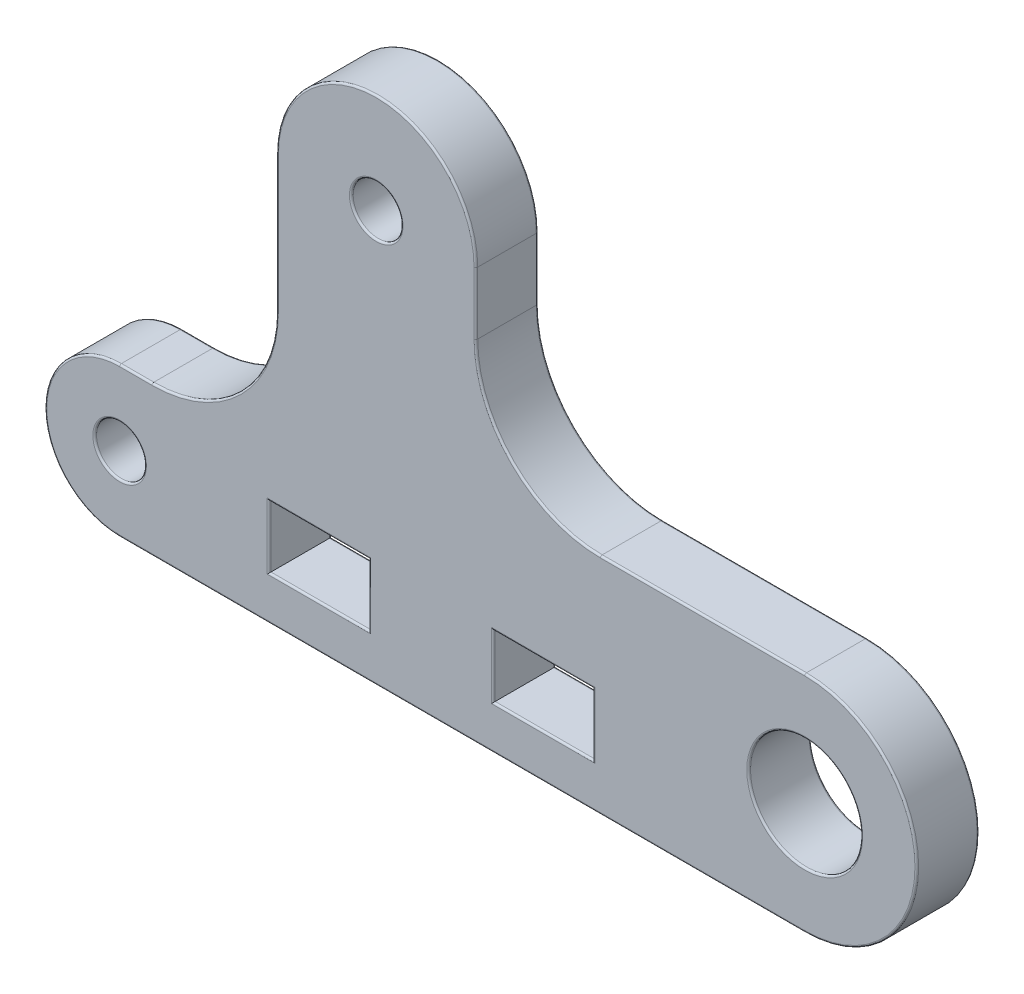
SolidWorks part; units mm, degrees
material "AISI 1020"
ref_plane "Front Plane" through (0, 0, 0) normal (0, 0, 1) x (1, 0, 0)
ref_plane "Top Plane" through (0, 0, 0) normal (0, 1, 0) x (1, 0, 0)
ref_plane "Right Plane" through (0, 0, 0) normal (1, 0, 0) x (0, 0, -1)
sketch "Sketch1" plane through (0, 0, 0) normal (0, 0, 1) x (1, 0, 0)
  line L0 (-27.5, 0) -> (27.5, 0)
  line L1 (-14.9, 33) -> (-14.9, 22)
  line L2 (-24.9, 12) -> (-27.5, 12)
  line L3 (1.1, 33) -> (1.1, 28)
  line L4 (11.1, 18) -> (27.5, 18)
  line L5 (-27.5, 6) -> (-15.5, 6) construction
  line L7 (-15.5, 3.5) -> (-7.5, 3.5)
  line L8 (-15.5, 3.5) -> (-15.5, 8.5)
  line L9 (-15.5, 8.5) -> (-7.5, 8.5)
  line L10 (-7.5, 3.5) -> (-7.5, 8.5)
  line L11 (2.5, 8.5) -> (10.5, 8.5)
  line L12 (2.5, 8.5) -> (2.5, 3.5)
  line L13 (2.5, 3.5) -> (10.5, 3.5)
  line L14 (10.5, 8.5) -> (10.5, 3.5)
  arc A0 (27.5, 0) -> (27.5, 18) centre (27.5, 9) ccw
  arc A1 (-27.5, 0) -> (-27.5, 12) centre (-27.5, 6) cw
  circle A2 centre (-27.5, 6) radius 2
  circle A3 centre (27.5, 9) radius 4.5
  circle A4 centre (-6.9, 33) radius 2
  circle A5 centre (-6.9, 33) radius 8 construction
  arc A6 (1.1, 28) -> (11.1, 18) centre (11.1, 28) ccw
  arc A7 (-14.9, 22) -> (-24.9, 12) centre (-24.9, 22) cw
  arc A8 (-14.9, 33) -> (1.1, 33) centre (-6.9, 33) cw
  point P3 (0, 0)
  dimension "D2" = 9
  dimension "D3" = 6
  dimension "D4" = 9
  dimension "D5" = 4
  dimension "D8" = 16
  dimension "D9" = 10
  dimension "D1" = 55
  dimension "D6" = 33
  dimension "D7" = 6.9
  dimension "D10" = 8
  dimension "D11" = 5
  dimension "D12" = 12
  dimension "D13" = 10
extrude "Boss-Extrude1" add sketch "Sketch1" along normal mid plane 5
fillet "Fillet1" radius 0.15 42 edges at (10.5, 6, -2.5) (6.5, 3.5, -2.5) (2.5, 6, -2.5) (6.5, 8.5, -2.5) (-7.5, 6, -2.5) (-11.5, 3.5, -2.5) (-15.5, 6, -2.5) (-11.5, 8.5, -2.5) (-4.9, 33, -2.5) (32, 9, -2.5) (0, 0, -2.5) (36.5, 9, -2.5) (19.3, 18, -2.5) (4.0289, 20.9289, -2.5) (1.1, 30.5, -2.5) (-6.9, 41, -2.5) (-14.9, 27.5, -2.5) (-17.8289, 14.9289, -2.5) (-26.2, 12, -2.5) (-33.5, 6, -2.5) (-25.5, 6, -2.5) (6.5, 3.5, 2.5) (10.5, 6, 2.5) (6.5, 8.5, 2.5) (2.5, 6, 2.5) (-4.9, 33, 2.5) (-25.5, 6, 2.5) (32, 9, 2.5) (-26.2, 12, 2.5) (-17.8289, 14.9289, 2.5) (-14.9, 27.5, 2.5) (-6.9, 41, 2.5) (1.1, 30.5, 2.5) (4.0289, 20.9289, 2.5) (19.3, 18, 2.5) (36.5, 9, 2.5) (0, 0, 2.5) (-33.5, 6, 2.5) (-11.5, 3.5, 2.5) (-7.5, 6, 2.5) (-11.5, 8.5, 2.5) (-15.5, 6, 2.5)
